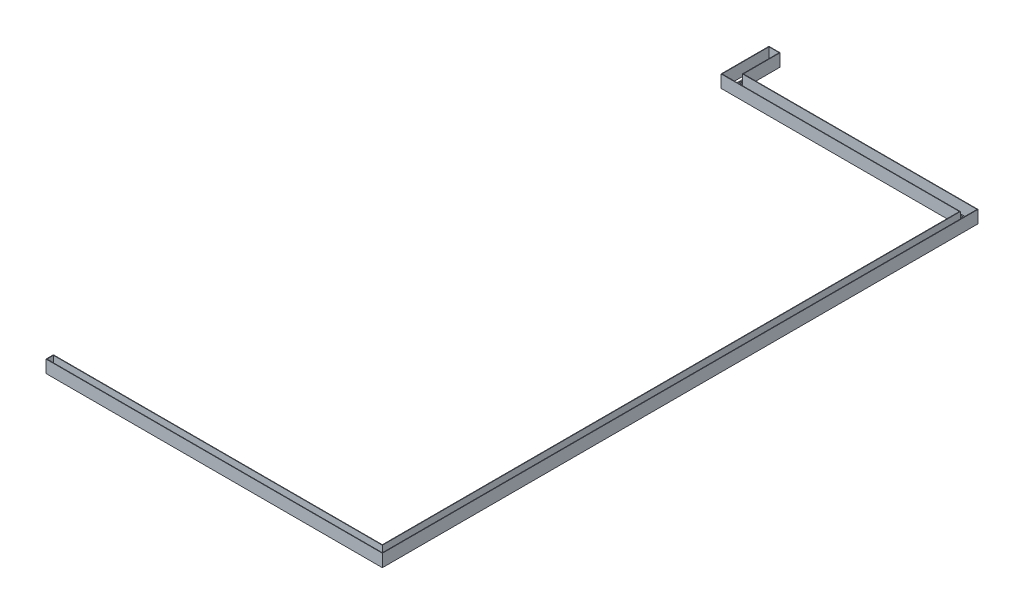
SolidWorks part; units mm, degrees
ref_plane "Alzado" through (0, 0, 0) normal (0, 0, 1) x (1, 0, 0)
ref_plane "Planta" through (0, 0, 0) normal (0, 1, 0) x (1, 0, 0)
ref_plane "Vista lateral" through (0, 0, 0) normal (1, 0, 0) x (0, 0, -1)
sketch "Croquis1" plane through (0, 0, 0) normal (0, 1, 0) x (1, 0, 0)
  line L0 (-3650, 36825) -> (-7150, 36825) construction
  line L1 (-7150, 36825) -> (-7150, 32875)
  line L2 (-7150, 36825) -> (-8350, 36825)
  line L3 (-8350, 36825) -> (-8350, 31675)
  line L4 (-7150, 32875) -> (18100, 32875)
  line L5 (-8350, 31675) -> (17300, 31675)
  line L6 (18100, 32875) -> (18100, -31225)
  line L7 (18100, -31225) -> (-18100, -31225)
  line L8 (17300, 31675) -> (17300, -30425)
  line L9 (17300, -30425) -> (-18100, -30425)
  line L10 (-18100, -37125) -> (-14800, -37125) construction
  line L11 (-14800, -37125) -> (-14800, -33825) construction
  line L12 (-14800, -33825) -> (-18100, -33825) construction
  line L13 (-18100, -33825) -> (-18100, -37125) construction
  line L14 (-18100, -33825) -> (-18100, -31875) construction
  line L15 (-18100, -31875) -> (-7748.74, -31875) construction
  line L16 (-18100, -33825) -> (-18100, -29725) construction
  line L17 (-18100, -29725) -> (-9550, -29725) construction
  line L18 (-18100, -37125) -> (-18100, -30825) construction
  line L19 (-18100, -30825) -> (-16871.3783, -30825) construction
  line L20 (0, 0) -> (0, 31675) construction
  line L21 (0, 0) -> (17300, 0) construction
  line L22 (-18100, -29725) -> (-18100, 0) construction
  line L23 (-18100, 0) -> (0, 0) construction
  line L24 (-18100, -31225) -> (-18100, -30425)
  line L25 (18050, 32825) -> (18050, -31175)
  line L26 (18050, -31175) -> (-18050, -31175)
  line L27 (-18050, -31175) -> (-18050, -30475)
  line L28 (17350, -30475) -> (-18050, -30475)
  line L29 (17350, 31725) -> (17350, -30475)
  line L30 (-8300, 31725) -> (17350, 31725)
  line L31 (-8300, 36775) -> (-8300, 31725)
  line L32 (-7200, 36775) -> (-8300, 36775)
  line L33 (-7200, 36775) -> (-7200, 32825)
  line L34 (-7200, 32825) -> (18050, 32825)
  line L35 (0, 31675) -> (0, 36775) construction
  line L36 (0, 36775) -> (-3650, 36825) construction
  line L37 (-3650, 36825) -> (-3704.1096, 32875) construction
  dimension "D1" = 3500
  dimension "D2" = 50
  dimension "D3" = 5150
  dimension "D4" = 1200
  dimension "D5" = 800
  dimension "D6" = 3300
  dimension "D7" = 3300
  dimension "D8" = 1950
  dimension "D9" = 4100
  dimension "D10" = 800
  dimension "D11" = 6300
  dimension "D12" = 400
  dimension "D13" = 64100
  dimension "D14" = 17300
  dimension "D15" = 29725
  dimension "D16" = 35400
  dimension "D17" = 1400
  dimension "D18" = 3950
  dimension "D19" = 3650
  dimension "D20" = 1200
extrude "Saliente-Extruir1" add sketch "Croquis1" against normal blind 1200 and the other way blind 150
sketch "Croquis2" plane through (-18100, 0, 0) normal (-1, 0, 0) x (0, 0, 1)
  circle A0 centre (31058.3242, -836.6593) radius 73.3748
  circle A1 centre (30561.6332, -836.6593) radius 84.6632
  circle A2 centre (30832.5556, -836.6593) radius 73.3748
sketch "Croquis3" plane through (0, 0, -36825) normal (0, 0, -1) x (-1, 0, 0)
  line L0 (7150, -1200) -> (7150, -525) construction
  line L1 (7150, 150) -> (7150, -1200) construction
  line L2 (7150, -525) -> (7847.0359, -525) construction
  line L3 (7847.0359, -525) -> (7847.0359, -1200) construction
  line L4 (7150, -1200) -> (8350, -1200) construction
  line L5 (7150, -862.5) -> (7847.0359, -862.5) construction
  circle A0 centre (7479.924, -862.5) radius 38.1
  circle A1 centre (7333.1511, -862.5) radius 38.1
  circle A2 centre (7635.9217, -862.5) radius 38.1
  circle A3 centre (7635.9217, -862.5) radius 32.0888
  circle A4 centre (7333.1511, -862.5) radius 35.4491
  circle A5 centre (7479.924, -862.5) radius 34.5116
  point P20 (7212.3527, -862.5)
  point P21 (7312.9465, -862.5)
  point P22 (7713.4925, -862.5)
  point P23 (7448.2908, -862.5)
  point P24 (7287.9802, -862.5)
  point P25 (7479.924, -862.5)
  point P26 (7635.9217, -862.5)
  point P27 (7333.1511, -862.5)
  dimension "D1" = 76.2
  dimension "D2" = 76.2
  dimension "D3" = 76.2
sketch3d "Croquis3D1"
  line L0 (-7621.1532, -862.5, -36825) -> (-7621.1532, -862.5, -32583.5544)
  line L1 (-7221.1532, -862.5, -32183.5544) -> (17187.3749, -862.5, -32183.5544)
  line L2 (17587.3749, -862.5, -31783.5544) -> (17587.3749, -862.5, 30292.3141)
  line L3 (17187.3749, -862.5, 30692.3141) -> (-18047.2424, -862.5, 30692.3141)
  arc A0 (17587.3749, -862.5, 30292.3141) -> (17187.3749, -862.5, 30692.3141) centre (17187.3749, -862.5, 30292.3141) ccw
  arc A1 (17187.3749, -862.5, -32183.5544) -> (17587.3749, -862.5, -31783.5544) centre (17187.3749, -862.5, -31783.5544) ccw
  arc A2 (-7621.1532, -862.5, -32583.5544) -> (-7221.1532, -862.5, -32183.5544) centre (-7221.1532, -862.5, -32583.5544) ccw
  point P7 (17587.3749, -862.5, 30692.3141)
  point P8 (17187.3749, -1262.5, 30292.3141)
  point P11 (17587.3749, -862.5, -32183.5544)
  point P12 (17187.3749, -1262.5, -31783.5544)
  point P15 (-7621.1532, -862.5, -32183.5544)
  point P16 (-7221.1532, -462.5, -32583.5544)
  point P17 (-7221.1532, -862.5, -32183.5544)
  dimension "D1" = 400
sweep "Barrer2" add profiles "Croquis3" path "Croquis3D1"
